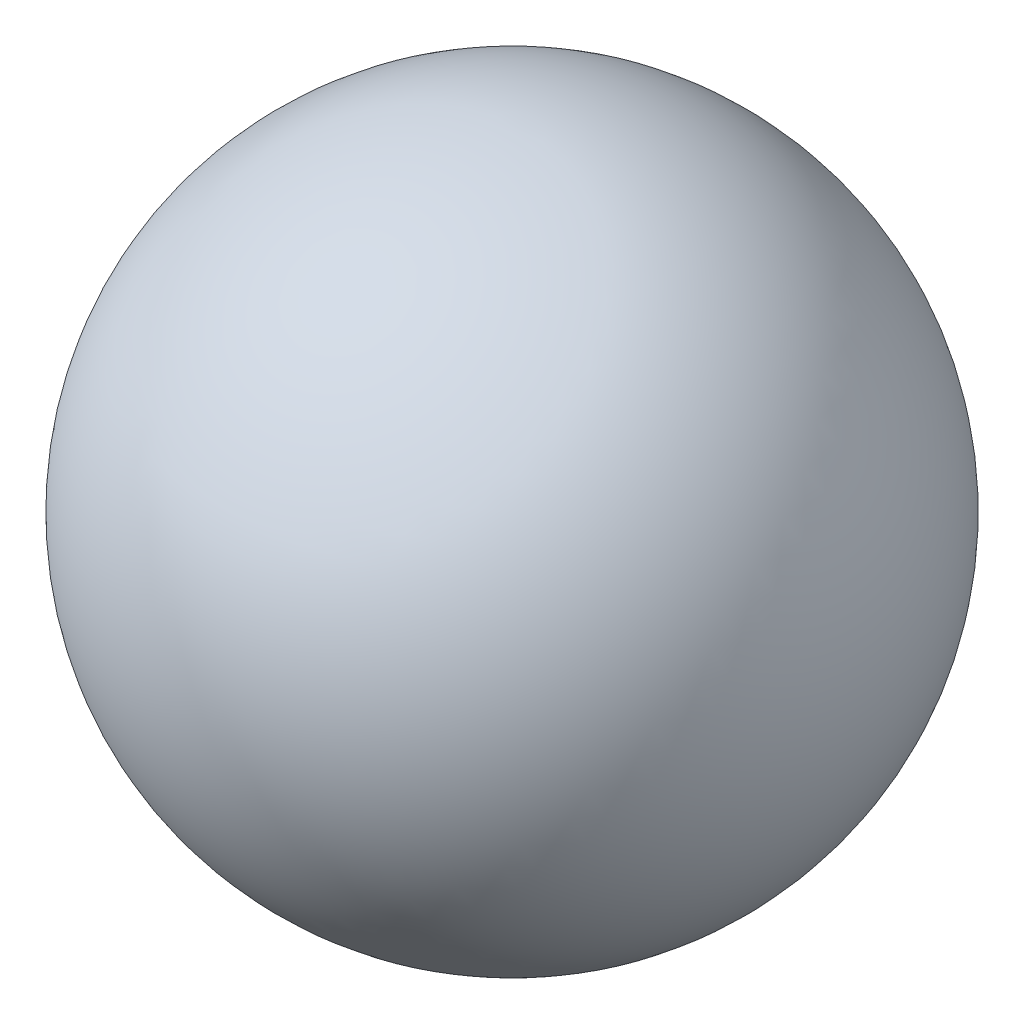
SolidWorks part; units mm, degrees
ref_plane "Plano frontal" through (0, 0, 0) normal (0, 0, 1) x (1, 0, 0)
ref_plane "Plano superior" through (0, 0, 0) normal (0, 1, 0) x (1, 0, 0)
ref_plane "Plano direito" through (0, 0, 0) normal (1, 0, 0) x (0, 0, -1)
sketch "Esboço1" plane through (0, 0, 0) normal (0, 0, 1) x (1, 0, 0)
  line L0 (0, 47.9068) -> (0, -67.325) construction
  line L1 (0, 26.1891) -> (0, -9.7091)
  arc A0 (0, 26.1891) -> (0, -9.7091) centre (0, 8.24) cw
revolve "Revolução1" add sketch "Esboço1" angle 360 about L0
